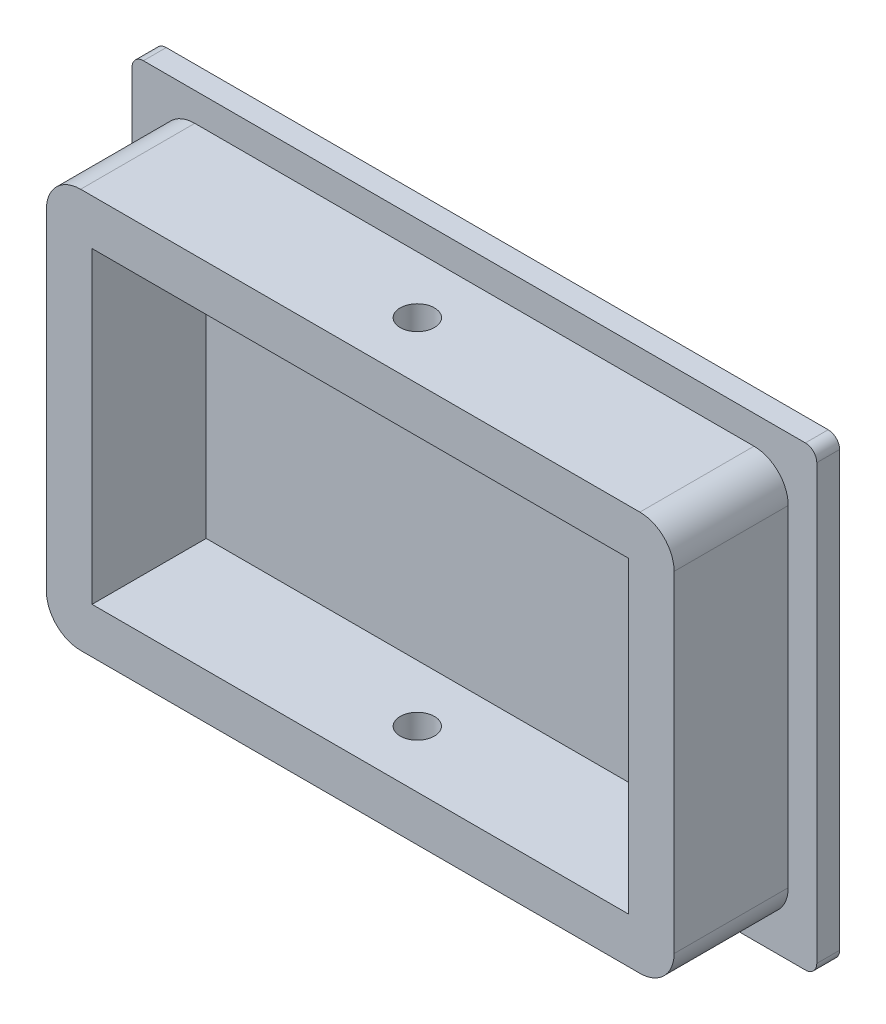
SolidWorks part; units mm, degrees
ref_plane "Plan de face" through (0, 0, 0) normal (0, 0, 1) x (1, 0, 0)
ref_plane "Plan de dessus" through (0, 0, 0) normal (0, 1, 0) x (1, 0, 0)
ref_plane "Plan de droite" through (0, 0, 0) normal (1, 0, 0) x (0, 0, -1)
sketch "Esquisse1" plane through (0, 0, 0) normal (0, 0, 1) x (1, 0, 0)
  line L1 (0, 0) -> (60, 0)
  line L2 (0, 0) -> (0, 40)
  line L3 (0, 40) -> (60, 40)
  line L4 (60, 0) -> (60, 40)
  dimension "D1" = 60
  dimension "D2" = 40
extrude "Boss.-Extru.1" add sketch "Esquisse1" along normal blind 2
sketch "Esquisse2" plane through (0, 0, 2) normal (0, 0, 1) x (1, 0, 0)
  line L12 (2.5, 37.5) -> (2.5, 2.5)
  line L13 (2.5, 2.5) -> (57.5, 2.5)
  line L14 (57.5, 2.5) -> (57.5, 37.5)
  line L15 (57.5, 37.5) -> (2.5, 37.5)
  line L16 (2.5, 37.5) -> (2.5, 2.5)
  line L17 (2.5, 2.5) -> (57.5, 2.5)
  line L18 (57.5, 2.5) -> (57.5, 37.5)
  line L19 (57.5, 37.5) -> (2.5, 37.5)
  dimension "D1" = 2.5
extrude "Boss.-Extru.2" add sketch "Esquisse2" along normal blind 10
fillet "Congé1" radius 3 4 edges at (2.5, 37.5, 7) (2.5, 2.5, 7) (57.5, 2.5, 7) (57.5, 37.5, 7)
fillet "Congé2" radius 1 4 edges at (0, 0, 1) (60, 0, 1) (60, 40, 1) (0, 40, 1)
sketch "Esquisse3" plane through (0, 0, 12) normal (0, 0, 1) x (1, 0, 0)
  line L12 (53.5, 33.5) -> (6.5, 33.5)
  line L13 (6.5, 33.5) -> (6.5, 6.5)
  line L14 (6.5, 6.5) -> (53.5, 6.5)
  line L15 (53.5, 6.5) -> (53.5, 33.5)
  line L16 (53.5, 33.5) -> (6.5, 33.5)
  line L17 (6.5, 33.5) -> (6.5, 6.5)
  line L18 (6.5, 6.5) -> (53.5, 6.5)
  line L19 (53.5, 6.5) -> (53.5, 33.5)
  dimension "D1" = 4
extrude "Enlèv. mat.-Extru.1" cut sketch "Esquisse3" against normal up to surface (10 mm away) up to face at (30, 20, 2)
sketch "Esquisse4" plane through (0, 37.5, 0) normal (0, 1, 0) x (1, 0, 0)
  line L0 (30, -2) -> (30, -7) construction
  line L1 (59, -2) -> (1, -2) construction
  circle A0 centre (30, -7) radius 1.5
  point P3 (29.4774, -2)
  point P6 (30, -2)
  dimension "D1" = 3
  dimension "D2" = 5
extrude "Enlèv. mat.-Extru.2" cut sketch "Esquisse4" against normal through all
